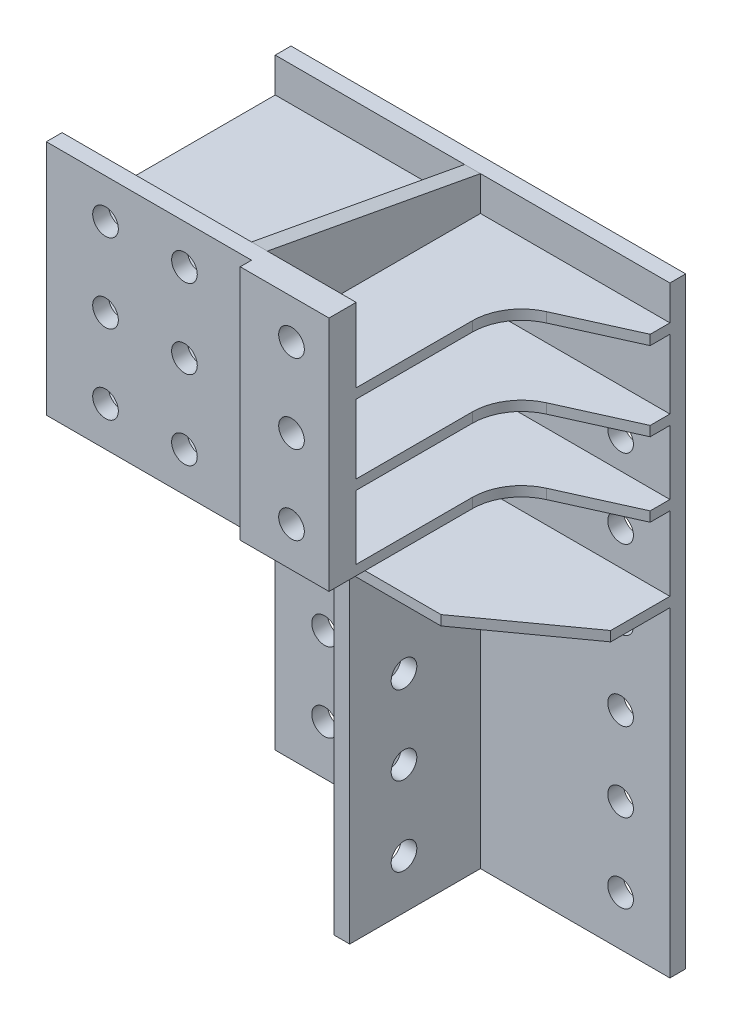
SolidWorks part; units mm, degrees
ref_plane "前视基准面" through (0, 0, 0) normal (0, 0, 1) x (1, 0, 0)
ref_plane "上视基准面" through (0, 0, 0) normal (0, 1, 0) x (1, 0, 0)
ref_plane "右视基准面" through (0, 0, 0) normal (1, 0, 0) x (0, 0, -1)
sketch "草图1" plane through (0, 0, 0) normal (0, 0, 1) x (1, 0, 0)
  line L1 (0, 0) -> (400, 0)
  line L2 (0, 0) -> (0, 610)
  line L3 (0, 610) -> (400, 610)
  line L4 (400, 0) -> (400, 610)
  dimension "D1" = 400
  dimension "D2" = 610
extrude "凸台-拉伸1" add sketch "草图1" along normal blind 16
sketch "草图2" plane through (0, 0, 16) normal (0, 0, 1) x (1, 0, 0)
  line L0 (0, 610) -> (0, 0) construction
  line L1 (0, 0) -> (400, 0) construction
  circle A0 centre (50, 50) radius 13
  dimension "D3" = 26
  dimension "D1" = 50
  dimension "D2" = 50
extrude "切除-拉伸1" cut sketch "草图2" against normal through all
pattern_linear "阵列(线性)1" count 2 spacing 300 along (1, 0, 0) count 6 spacing 80 along (0, 1, 0) of "切除-拉伸1"
sketch "草图3" plane through (0, 0, 16) normal (0, 0, 1) x (1, 0, 0)
  line L0 (200, -390) -> (200, 49610) construction
  line L1 (400, 610) -> (0, 610) construction
  line L2 (0, 0) -> (400, 0) construction
  line L3 (192, 0) -> (208, 0)
  line L4 (192, 0) -> (192, 650)
  line L5 (192, 650) -> (208, 650)
  line L6 (208, 0) -> (208, 650)
  point P5 (200, 610)
  dimension "D1" = 650
  dimension "D2" = 16
extrude "凸台-拉伸2" add sketch "草图3" along normal blind 216
sketch "草图4" plane through (208, 0, 0) normal (1, 0, 0) x (0, 0, -1)
  line L0 (-232, 650) -> (-16, 650)
  line L1 (-16, 650) -> (-16, 610)
  line L2 (-16, 610) -> (-232, 650)
  line L3 (-198.5, 410) -> (-232, 410)
  line L4 (-232, 0) -> (-232, 650) construction
  line L5 (-232, 410) -> (-232, 0)
  line L6 (-232, 0) -> (-148.5, 0)
  line L7 (-232, 0) -> (-16, 0) construction
  line L8 (-148.5, 0) -> (-148.5, 360)
  line L9 (-16, 0) -> (-16, 610) construction
  arc A0 (-198.5, 410) -> (-148.5, 360) centre (-198.5, 360) cw
  circle A1 centre (-93.5, 210) radius 13
  circle A2 centre (-93.5, 130) radius 13
  circle A3 centre (-93.5, 50) radius 13
  dimension "D3" = 50
  dimension "D4" = 26
  dimension "D1" = 240
  dimension "D2" = 132.5
  dimension "D5" = 50
  dimension "D6" = 80
  dimension "D7" = 80
  dimension "D8" = 138.5
extrude "切除-拉伸2" cut sketch "草图4" against normal through all
sketch "草图5" plane through (0, 0, 16) normal (0, 0, 1) x (1, 0, 0)
  line L0 (0, 610) -> (0, 0) construction
  line L1 (0, 575) -> (400, 575)
  line L2 (0, 575) -> (0, 565)
  line L3 (0, 565) -> (400, 565)
  line L4 (400, 575) -> (400, 565)
  line L5 (400, 0) -> (400, 610) construction
  line L6 (400, 610) -> (208, 610) construction
  line L7 (0, 495) -> (400, 495)
  line L8 (0, 495) -> (0, 485)
  line L9 (0, 485) -> (400, 485)
  line L10 (400, 495) -> (400, 485)
  line L11 (0, 420) -> (400, 420)
  line L12 (0, 420) -> (0, 410)
  line L13 (0, 410) -> (400, 410)
  line L14 (400, 420) -> (400, 410)
  dimension "D1" = 10
  dimension "D2" = 10
  dimension "D3" = 10
  dimension "D4" = 35
  dimension "D5" = 80
  dimension "D6" = 75
extrude "凸台-拉伸3" add sketch "草图5" along normal blind 216
sketch "草图6" plane through (0, 410, 0) normal (0, -1, 0) x (-1, 0, 0)
  line L0 (-298, -232) -> (-298, -114.3004)
  line L1 (0, -232) -> (-400, -232) construction
  line L2 (-327.4446, -68.7211) -> (-400, -36)
  line L3 (-400, -232) -> (-400, -16) construction
  line L4 (-400, -36) -> (-400, -232)
  line L5 (-400, -232) -> (-298, -232)
  line L6 (-208, -148.5) -> (-208, -16) construction
  line L7 (-208, -16) -> (-400, -16) construction
  line L8 (-208, -16) -> (-400, -16) construction
  arc A0 (-327.4446, -68.7211) -> (-298, -114.3004) centre (-348, -114.3004) cw
  point P17 (-298, -82)
  dimension "D4" = 50
  dimension "D1" = 90
  dimension "D2" = 20
  dimension "D3" = 66
extrude "切除-拉伸3" cut sketch "草图6" against normal through all
sketch "草图7" plane through (0, 0, 16) normal (0, 0, 1) x (1, 0, 0)
  line L0 (0, 410) -> (0, 0) construction
  line L1 (0, 335) -> (400, 335)
  line L2 (0, 335) -> (0, 325)
  line L3 (0, 325) -> (400, 325)
  line L4 (400, 335) -> (400, 325)
  line L5 (400, 0) -> (400, 410) construction
  line L6 (192, 420) -> (0, 420) construction
  dimension "D1" = 85
  dimension "D2" = 10
extrude "凸台-拉伸4" add sketch "草图7" along normal blind 132
sketch "草图8" plane through (0, 325, 0) normal (0, -1, 0) x (-1, 0, 0)
  line L0 (-400, -148) -> (-300, -148)
  line L1 (-208, -148) -> (-400, -148) construction
  line L2 (-300, -148) -> (-400, -76)
  line L3 (-400, -148) -> (-400, -16) construction
  line L4 (-400, -76) -> (-400, -148)
  line L5 (-208, -16) -> (-400, -16) construction
  line L6 (0, -148) -> (-100, -148)
  line L7 (0, -148) -> (-192, -148) construction
  line L8 (-100, -148) -> (0, -76)
  line L9 (0, -148) -> (0, -16) construction
  line L10 (0, -76) -> (0, -148)
  dimension "D1" = 100
  dimension "D2" = 60
extrude "切除-拉伸4" cut sketch "草图8" against normal blind 10
sketch "草图9" plane through (0, 0, 232) normal (0, 0, 1) x (1, 0, 0)
  line L0 (208, 650) -> (192, 650) construction
  line L1 (0, 650) -> (298, 650)
  line L2 (0, 650) -> (0, 410)
  line L3 (0, 410) -> (298, 410)
  line L4 (298, 650) -> (298, 410)
  line L5 (0, 565) -> (0, 495) construction
  dimension "D1" = 240
  dimension "D2" = 298
extrude "凸台-拉伸5" add sketch "草图9" along normal blind 16
sketch "草图10" plane through (0, 0, 248) normal (0, 0, 1) x (1, 0, 0)
  line L0 (0, 650) -> (0, 410) construction
  line L1 (298, 650) -> (0, 650) construction
  circle A0 centre (60, 610) radius 13
  dimension "D1" = 26
  dimension "D2" = 60
  dimension "D3" = 40
extrude "切除-拉伸5" cut sketch "草图10" against normal blind 16
pattern_linear "阵列(线性)2" count 2 spacing 80 along (1, 0, 0) of "切除-拉伸5"
pattern_linear "阵列(线性)3" count 2 spacing 200 along (1, 0, 0) of "切除-拉伸5"
pattern_linear "阵列(线性)4" count 3 spacing 80 along (0, -1, 0) of "切除-拉伸5", "阵列(线性)2", "阵列(线性)3"
sketch "草图11" plane through (0, 0, 248) normal (0, 0, 1) x (1, 0, 0)
  line L0 (0, 410) -> (298, 410) construction
  line L1 (298, 650) -> (208, 650)
  line L2 (298, 650) -> (298, 410)
  line L3 (298, 410) -> (208, 410)
  line L4 (208, 650) -> (208, 410)
  line L5 (208, 335) -> (208, 410) construction
  circle A0 centre (260, 610) radius 13
  circle A1 centre (260, 530) radius 13
  circle A2 centre (260, 450) radius 13
  circle A3 centre (260, 610) radius 13 construction
  circle A4 centre (260, 530) radius 13 construction
  circle A5 centre (260, 450) radius 13 construction
extrude "凸台-拉伸6" add sketch "草图11" along normal blind 11.5
